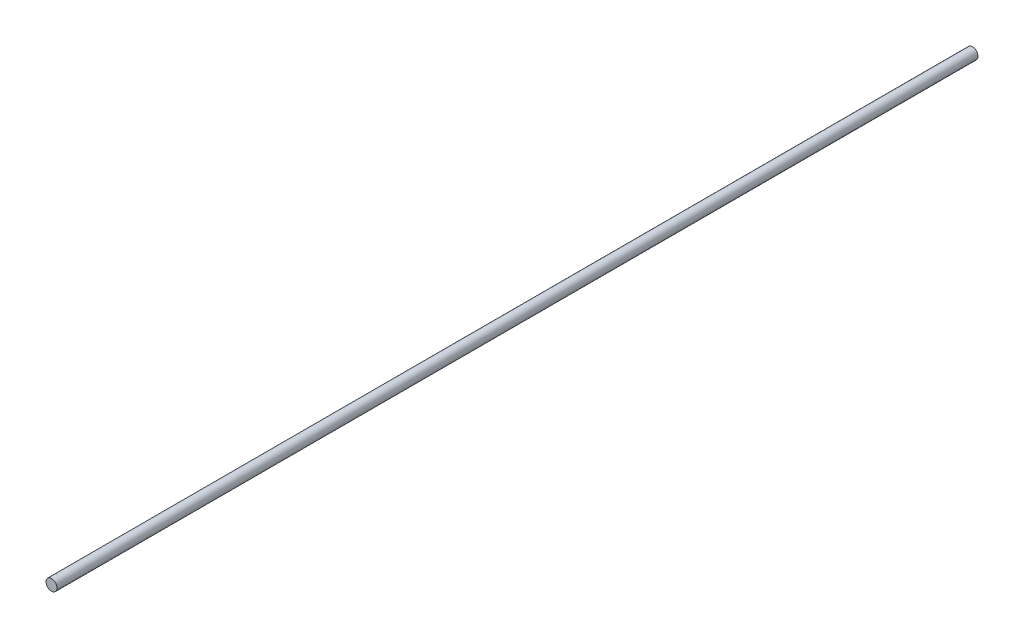
SolidWorks part; units mm, degrees
ref_plane "Front Plane" through (0, 0, 0) normal (0, 0, 1) x (1, 0, 0)
ref_plane "Top Plane" through (0, 0, 0) normal (0, 1, 0) x (1, 0, 0)
ref_plane "Right Plane" through (0, 0, 0) normal (1, 0, 0) x (0, 0, -1)
sketch "Sketch1" plane through (0, 0, 0) normal (0, 0, 1) x (1, 0, 0)
  circle A0 centre (0, 0) radius 1.2
  dimension "D1" = 2.4
extrude "Boss-Extrude1" add sketch "Sketch1" along normal blind 200
